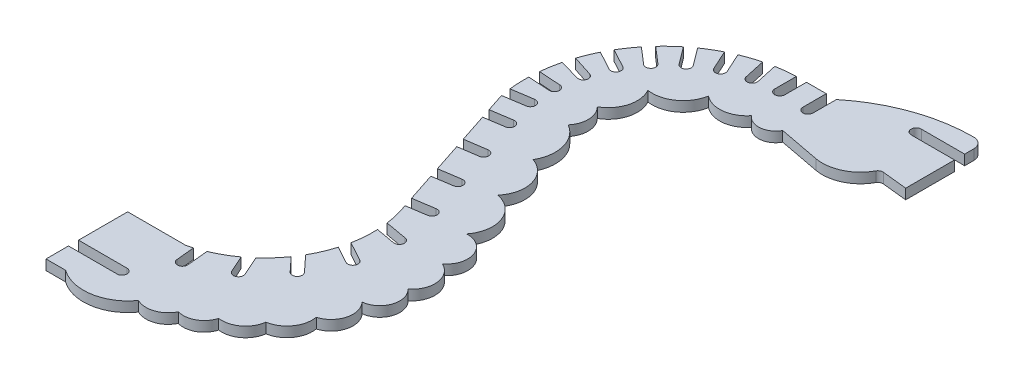
SolidWorks part; units mm, degrees
ref_plane "Front Plane" through (0, 0, 0) normal (0, 0, 1) x (1, 0, 0)
ref_plane "Top Plane" through (0, 0, 0) normal (0, 1, 0) x (1, 0, 0)
ref_plane "Right Plane" through (0, 0, 0) normal (1, 0, 0) x (0, 0, -1)
sketch "Sketch2" plane through (0, 0, 0) normal (0, 1, 0) x (1, 0, 0)
  line L0 (30.5917, -19.7066) -> (10.7781, -19.7066)
  line L1 (33.5917, -22.7066) -> (33.5917, -25.4201)
  line L2 (33.5917, -25.4201) -> (20.7417, -25.4201)
  line L3 (20.7417, -28.4201) -> (33.5917, -28.4201)
  line L4 (33.5917, -28.4201) -> (33.5917, -42.8901)
  line L5 (33.5917, -42.8901) -> (26.2103, -42.1143)
  line L6 (25.8967, -45.0978) -> (33.5917, -45.9066)
  line L7 (33.5917, -45.9066) -> (33.5917, -49.9666)
  line L8 (33.5917, -49.9666) -> (8.1291, -49.9666)
  line L9 (-13.2283, -50.6294) -> (-13.2283, -45.1294)
  line L10 (-38.0968, -90.3449) -> (-15.0449, -119.6181) construction
  line L11 (-16.2283, -45.1294) -> (-16.2283, -51.5914)
  line L12 (-21.75, -54.7438) -> (-23.977, -49.7148)
  line L13 (-26.7201, -50.9295) -> (-24.1036, -56.8382)
  line L14 (-27.876, -61.9563) -> (-31.9485, -58.2597)
  line L15 (-33.9648, -60.4811) -> (-29.18, -64.8243)
  line L16 (-30.557, -71.0316) -> (-35.7774, -69.3005)
  line L17 (-36.7216, -72.1481) -> (-30.588, -74.1819)
  line L18 (-1.8595, -49.9666) -> (0.2542, -45.786)
  line L19 (-2.4231, -44.4324) -> (-5.2212, -49.9666)
  line L20 (8.1291, -49.9666) -> (10.2428, -45.786)
  line L21 (7.5656, -44.4324) -> (4.7675, -49.9666)
  line L22 (4.7675, -49.9666) -> (-1.8595, -49.9666)
  line L23 (-5.2212, -49.9666) -> (-7.7629, -49.9666)
  line L24 (8.977, -22.5761) -> (13.5917, -32.1352)
  line L25 (-7.9083, -19.7066) -> (-7.9083, -28.4201)
  line L26 (-7.9083, -28.4201) -> (-17.7173, -27.1758)
  line L27 (-24.1872, -25.2122) -> (-23.0538, -31.1352)
  line L28 (-22.371, -24.1878) -> (-20.4329, -25.9321)
  line L29 (-38.0926, -32.0919) -> (-35.6757, -33.0702)
  line L30 (-39.4504, -33.6745) -> (-36.3639, -38.8553)
  line L31 (-23.0538, -31.1352) -> (-32.6987, -33.3127)
  line L32 (-50.1737, -44.8862) -> (-47.568, -44.981)
  line L33 (-50.9099, -46.8371) -> (-46.2408, -50.6538)
  line L34 (-36.3639, -38.8553) -> (-44.6869, -44.1931)
  line L35 (-57.1639, -61.035) -> (-54.6822, -60.235)
  line L36 (-57.1902, -63.12) -> (-51.4991, -65.1145)
  line L37 (-46.2408, -50.6538) -> (-52.2429, -58.5113)
  line L38 (-58.2242, -78.5997) -> (-56.1645, -77.001)
  line L39 (-57.5375, -80.5686) -> (-51.5074, -80.5014)
  line L40 (-51.4991, -65.1145) -> (-54.4597, -74.5484)
  line L41 (-35.2032, -82.0735) -> (-27.7919, -84.6414)
  line L42 (-34.2211, -79.2389) -> (-29.1162, -81.0076)
  line L43 (-29.3337, -80.4151) -> (-34.808, -80.9462)
  line L44 (-34.5184, -83.9321) -> (-28.0865, -83.3082)
  line L45 (-27.7919, -84.6414) -> (-23.8627, -95.4227)
  line L46 (-29.9498, -96.4886) -> (-22.5384, -99.0565)
  line L47 (-28.9676, -93.654) -> (-23.8627, -95.4227)
  line L48 (-24.6963, -110.9037) -> (-17.2849, -113.4716)
  line L49 (-23.7142, -108.0691) -> (-18.6093, -109.8378)
  line L50 (-19.4428, -125.3189) -> (-12.8043, -127.6189)
  line L51 (-18.4607, -122.4842) -> (-13.6103, -124.1647)
  line L52 (-17.6104, -135.4043) -> (-11.761, -138.9742)
  line L53 (-16.0476, -132.8435) -> (-11.8298, -135.4176)
  line L55 (-17.9659, -145.6487) -> (-13.1058, -150.2901)
  line L56 (-15.894, -143.4791) -> (-12.4305, -146.7867)
  line L57 (-13.2072, -136.8993) -> (-8.1023, -138.668)
  line L58 (-14.1894, -139.734) -> (-6.778, -142.3018)
  line L59 (-20.4932, -155.5829) -> (-16.78, -161.0812)
  line L60 (-18.0071, -153.9039) -> (-15.3857, -157.7855)
  line L61 (-25.0765, -164.7517) -> (-22.6311, -170.882)
  line L62 (-22.29, -163.6402) -> (-20.5743, -167.9412)
  line L63 (-31.5058, -172.7353) -> (-30.5908, -178.2262)
  line L64 (-28.5466, -172.2422) -> (-27.8723, -176.2883)
  line L65 (-39.4867, -179.1681) -> (-39.7092, -183.6785)
  line L66 (-36.4904, -179.3159) -> (-36.6228, -182.0006)
  line L67 (-47.9916, -182.1905) -> (-48.2552, -187.533)
  line L68 (-44.9953, -182.3383) -> (-45.1896, -186.2772)
  line L69 (-45.7574, -184.5372) -> (-47.0955, -189.4931)
  line L70 (-48.6536, -183.7552) -> (-50.485, -190.538)
  line L71 (-52.7944, -97.0434) -> (-47.044, -95.2268)
  line L72 (-54.0236, -95.3591) -> (-52.5174, -93.2307)
  line L73 (-51.5074, -80.5014) -> (-51.5989, -90.3886)
  line L74 (-48.331, -111.7688) -> (-42.5806, -109.9522)
  line L75 (-49.5602, -110.0844) -> (-48.054, -107.9561)
  line L76 (-47.044, -95.2268) -> (-47.1355, -105.1139)
  line L77 (-43.8676, -126.4942) -> (-38.1172, -124.6776)
  line L78 (-45.0969, -124.8098) -> (-43.5906, -122.6815)
  line L79 (-42.5806, -109.9522) -> (-42.6721, -119.8393)
  line L80 (-38.1172, -124.6776) -> (-38.1172, -132.1134)
  line L81 (-49.4878, -147.4069) -> (-42.6952, -147.4697)
  line L82 (-75.5719, -158.8868) -> (-75.5719, -178.7297)
  line L83 (-22.5384, -99.0565) -> (-18.6093, -109.8378)
  line L84 (-17.2849, -113.4716) -> (-15.0449, -119.6181)
  line L85 (-75.5719, -181.7068) -> (-61.4778, -181.7068)
  line L86 (-61.2167, -178.7297) -> (-75.5719, -178.7297)
  line L87 (-75.5719, -181.7068) -> (-75.5719, -190.1036)
  arc A0 (-13.2283, -45.1294) -> (-16.2283, -45.1294) centre (-14.7283, -45.1294) ccw
  arc A1 (20.7417, -25.4201) -> (20.7417, -28.4201) centre (20.7417, -26.9201) ccw
  arc A2 (26.2103, -42.1143) -> (25.8967, -45.0978) centre (26.0535, -43.6061) ccw
  arc A3 (-7.7629, -49.9666) -> (-13.2283, -50.6294) centre (-7.7629, -72.8316) ccw
  arc A4 (-15.0449, -119.6181) -> (-13.6103, -124.1647) centre (-66.1611, -138.247) cw
  arc A5 (-25.7152, -174.6342) -> (-27.8723, -176.2883) centre (-79.6425, -106.5423) cw
  arc A6 (-23.977, -49.7148) -> (-26.7201, -50.9295) centre (-25.3485, -50.3222) ccw
  arc A7 (-31.9485, -58.2597) -> (-33.9648, -60.4811) centre (-32.9567, -59.3704) ccw
  arc A8 (-35.7774, -69.3005) -> (-36.7216, -72.1481) centre (-36.2495, -70.7243) ccw
  arc A9 (0.2542, -45.786) -> (-2.4231, -44.4324) centre (-1.0844, -45.1092) ccw
  arc A10 (10.2428, -45.786) -> (7.5656, -44.4324) centre (8.9042, -45.1092) ccw
  arc A11 (-20.4329, -25.9321) -> (-17.7173, -27.1758) centre (-17.0881, -22.2156) ccw
  arc A12 (-16.2283, -51.5914) -> (-21.75, -54.7438) centre (-7.7629, -72.8316) ccw
  arc A13 (-24.1036, -56.8382) -> (-27.876, -61.9563) centre (-7.7629, -72.8316) ccw
  arc A14 (-29.18, -64.8243) -> (-30.557, -71.0316) centre (-7.7629, -72.8316) ccw
  arc A15 (-30.588, -74.1819) -> (-29.1162, -81.0076) centre (-7.7629, -72.8316) ccw
  arc A16 (13.5917, -32.1352) -> (-6.482, -19.3651) centre (14.3476, -8.7848) cw
  arc A17 (-6.482, -19.3651) -> (-7.9083, -19.7066) centre (-7.1543, -19.7066) ccw
  arc A18 (-22.371, -24.1878) -> (-24.1872, -25.2122) centre (-23.1068, -25.0054) ccw
  arc A19 (-35.6757, -33.0702) -> (-32.6987, -33.3127) centre (-33.7998, -28.4354) ccw
  arc A20 (-38.0926, -32.0919) -> (-39.4504, -33.6745) centre (-38.5053, -33.1115) ccw
  arc A21 (-47.568, -44.981) -> (-44.6869, -44.1931) centre (-47.3861, -39.9843) ccw
  arc A22 (-50.1737, -44.8862) -> (-50.9099, -46.8371) centre (-50.2137, -45.9855) ccw
  arc A23 (-54.6822, -60.235) -> (-52.2429, -58.5113) centre (-56.2163, -55.4761) ccw
  arc A24 (-57.1639, -61.035) -> (-57.1902, -63.12) centre (-56.8264, -62.0819) ccw
  arc A25 (-56.1645, -77.001) -> (-54.4597, -74.5484) centre (-59.2303, -73.0512) ccw
  arc A26 (-58.2242, -78.5997) -> (-57.5375, -80.5686) centre (-57.5498, -79.4687) ccw
  arc A27 (-34.808, -80.9462) -> (-34.5184, -83.9321) centre (-34.6632, -82.4391) ccw
  arc A28 (-35.2032, -82.0735) -> (-34.2211, -79.2389) centre (-34.7122, -80.6562) cw
  arc A29 (-29.9498, -96.4886) -> (-28.9676, -93.654) centre (-29.4587, -95.0713) cw
  arc A30 (-24.6963, -110.9037) -> (-23.7142, -108.0691) centre (-24.2052, -109.4864) cw
  arc A31 (-19.4428, -125.3189) -> (-18.4607, -122.4842) centre (-18.9518, -123.9015) cw
  arc A32 (-12.8043, -127.6189) -> (-11.8298, -135.4176) centre (-66.1611, -138.247) cw
  circle A33 centre (-7.7629, -72.8316) radius 44.4118 construction
  arc A34 (-17.6104, -135.4043) -> (-16.0476, -132.8435) centre (-16.829, -134.1239) cw
  arc A35 (-14.1894, -139.734) -> (-13.2072, -136.8993) centre (-13.6983, -138.3166) cw
  arc A36 (-17.9659, -145.6487) -> (-15.894, -143.4791) centre (-16.93, -144.5639) cw
  arc A37 (-20.4932, -155.5829) -> (-18.0071, -153.9039) centre (-19.2502, -154.7434) cw
  arc A38 (-25.0765, -164.7517) -> (-22.29, -163.6402) centre (-23.6833, -164.196) cw
  arc A39 (-31.5058, -172.7353) -> (-28.5466, -172.2422) centre (-30.0262, -172.4888) cw
  arc A40 (-39.4867, -179.1681) -> (-36.4904, -179.3159) centre (-37.9885, -179.242) cw
  arc A41 (-47.9916, -182.1905) -> (-44.9953, -182.3383) centre (-46.4934, -182.2644) cw
  arc A42 (-48.6536, -183.7552) -> (-45.7574, -184.5372) centre (-47.2055, -184.1462) cw
  arc A43 (-52.5174, -93.2307) -> (-51.5989, -90.3886) centre (-56.5987, -90.3423) ccw
  arc A44 (-54.0236, -95.3591) -> (-52.7944, -97.0434) centre (-53.1257, -95.9945) ccw
  arc A45 (-49.5602, -110.0844) -> (-48.331, -111.7688) centre (-48.6624, -110.7199) ccw
  arc A46 (-48.054, -107.9561) -> (-47.1355, -105.1139) centre (-52.1353, -105.0677) ccw
  arc A47 (-45.0969, -124.8098) -> (-43.8676, -126.4942) centre (-44.199, -125.4453) ccw
  arc A48 (-43.5906, -122.6815) -> (-42.6721, -119.8393) centre (-47.6719, -119.7931) ccw
  arc A49 (-38.1172, -132.1134) -> (-49.6306, -145.3128) centre (-51.44, -132.1134) cw
  arc A50 (-49.6306, -145.3128) -> (-49.4878, -147.4069) centre (-49.4878, -146.3549) ccw
  arc A51 (-42.6952, -147.4697) -> (-57.0275, -157.7653) centre (-53.632, -147.3685) cw
  arc A52 (-57.0275, -157.7653) -> (-77.6013, -143.4683) centre (-43.5012, -116.3489) cw
  arc A53 (-77.6013, -143.4683) -> (-80.2278, -144.5253) centre (-78.7573, -144.3877) ccw
  arc A54 (-80.2278, -144.5253) -> (-75.5719, -158.8868) centre (-45.8128, -141.3035) ccw
  arc A55 (-22.6311, -170.882) -> (-25.7152, -174.6342) centre (-66.1611, -138.247) cw
  arc A56 (-30.5908, -178.2262) -> (-36.6228, -182.0006) centre (-79.6425, -106.5423) cw
  arc A57 (-39.7092, -183.6785) -> (-45.1896, -186.2772) centre (-79.6425, -106.5423) cw
  arc A58 (-48.2552, -187.533) -> (-82.1004, -193.3675) centre (-79.6425, -106.5423) cw construction
  arc A59 (-16.78, -161.0812) -> (-20.5743, -167.9412) centre (-66.1611, -138.247) cw
  arc A60 (-13.1058, -150.2901) -> (-15.3857, -157.7855) centre (-66.1611, -138.247) cw
  arc A61 (-11.761, -138.9742) -> (-12.4305, -146.7867) centre (-66.1611, -138.247) cw
  arc A62 (-61.4778, -181.7068) -> (-61.2167, -178.7297) centre (-61.2167, -180.2297) ccw
  arc A63 (10.7781, -19.7066) -> (8.977, -22.5761) centre (10.7781, -21.7066) ccw
  arc A64 (30.5917, -19.7066) -> (33.5917, -22.7066) centre (30.5917, -22.7066) cw
  arc A65 (-48.2552, -187.533) -> (-72.3189, -193.093) centre (-79.6425, -106.5423) cw
  arc A66 (-72.3189, -193.093) -> (-75.5719, -190.1036) centre (-72.5719, -190.1036) cw
  point P30 (22.2417, -26.9201)
  point P31 (24.5617, -43.4493)
  point P36 (-14.7283, -43.6294)
  point P208 (-79.3087, -143.0175)
  point P222 (33.5917, -19.7066)
  point P223 (-75.5719, -193.3068)
  dimension "D1" = 22.865
  dimension "D4" = 54.405
  dimension "D6" = 40
  dimension "D7" = 86.86
  dimension "D12" = 1.5
  dimension "D10" = 56.11
  dimension "D22" = 41.5
  dimension "D23" = 187.229
  dimension "D25" = 1.1
  dimension "D27" = 5
  dimension "D33" = 6.1298
  dimension "D40" = 1.5
  dimension "D41" = 1.5
  dimension "D39" = 6.778
  dimension "D42" = 7.1543
  dimension "D43" = 8.1023
  dimension "D44" = 11.761
  dimension "D45" = 12.8043
  dimension "D46" = 13.2072
  dimension "D47" = 13.6103
  dimension "D48" = 15.3857
  dimension "D49" = 15.894
  dimension "D50" = 21.75
  dimension "D51" = 27.8723
  dimension "D74" = 2
  dimension "D75" = 3
  dimension "D76" = 3
  dimension "D2" = 120
  dimension "D3" = 37.26
  dimension "D5" = 62
  dimension "D8" = 46.82
  dimension "D9" = 4.06
  dimension "D11" = 9.03
  dimension "D13" = 6
  dimension "D14" = 11.35
  dimension "D15" = 30.26
  dimension "D16" = 14.47
  dimension "D17" = 7
  dimension "D21" = 20
  dimension "D24" = 10.833
  dimension "D26" = 1
  dimension "D31" = 50.35
  dimension "D32" = 4.8575
  dimension "D34" = 11.0799
  dimension "D35" = 2
  dimension "D37" = 34.42
  dimension "D38" = 11.6
  dimension "D52" = 42.6952
  dimension "D53" = 43.5012
  dimension "D54" = 44.9953
  dimension "D55" = 45.1896
  dimension "D56" = 45.8128
  dimension "D57" = 46.4934
  dimension "D58" = 49.4878
  dimension "D59" = 49.6306
  dimension "D60" = 51.44
  dimension "D61" = 53.632
  dimension "D62" = 57.0275
  dimension "D63" = 61.2167
  dimension "D64" = 61.4778
  dimension "D65" = 79.3087
  dimension "D66" = 8.7848
  dimension "D67" = 33.0668
  dimension "D68" = 72.8316
  dimension "D69" = 5.6615
  dimension "D70" = 27.1379
  dimension "D71" = 9.9886
  dimension "D72" = 5.9141
  dimension "D73" = 64.231
  dimension "D20" = 2
  dimension "D29" = 5
  dimension "D36" = 3
  dimension "D19" = 2
  dimension "D28" = 5
  dimension "D18" = 5
  dimension "D30" = 8
sketch "Sketch3" plane through (0, 0, 0) normal (0, 1, 0) x (1, 0, 0)
  line L0 (0.5917, -30.4201) -> (0.5917, -37.3301)
  line L1 (-2.4083, -37.3301) -> (-2.4083, -30.4201)
  line L2 (33.5917, -42.8901) -> (26.2103, -42.1143)
  line L3 (-2.4083, -30.4201) -> (-8.2583, -30.4201)
  line L4 (-8.2583, -30.4201) -> (-8.2583, -36.8301)
  line L5 (-11.2583, -36.8301) -> (-11.2583, -30.4201)
  line L6 (-50.0406, -78.9753) -> (-35.5907, -122.9508) construction
  line L7 (-75.5719, -178.7297) -> (-75.5719, -164.1797)
  line L8 (-75.5719, -164.1797) -> (-58.3719, -164.1797)
  line L9 (12.6752, -48.6069) -> (0.5917, -46.3094)
  line L10 (-69.7587, -188.3668) -> (-75.5719, -188.3668)
  line L11 (-75.5719, -181.7068) -> (-75.5719, -190.1036) construction
  line L12 (-75.5719, -188.3668) -> (-75.5719, -181.7068)
  line L13 (-17.0347, -31.0436) -> (-15.6668, -37.306)
  line L14 (-18.5977, -37.9462) -> (-19.9656, -31.6838)
  line L15 (-25.4759, -33.5257) -> (-22.8031, -39.3519)
  line L16 (-25.5298, -40.6028) -> (-28.2027, -34.7767)
  line L17 (-33.1929, -37.752) -> (-29.3384, -42.8736)
  line L18 (-31.7353, -44.6776) -> (-35.5899, -39.556)
  line L19 (-39.8303, -43.5278) -> (-34.9715, -47.7088)
  line L20 (-36.9283, -49.9828) -> (-41.7871, -45.8018)
  line L21 (-45.0822, -50.587) -> (-39.4431, -53.6348)
  line L22 (-40.8695, -56.274) -> (-46.5086, -53.2262)
  line L23 (-42.547, -60.3785) -> (-48.6449, -58.4179)
  line L24 (-43.3774, -63.2613) -> (-49.537, -61.4871)
  line L25 (-50.5366, -67.2104) -> (-44.1403, -67.6293)
  line L26 (-44.3363, -70.6229) -> (-50.7326, -70.204)
  line L27 (-50.4879, -76.0088) -> (-44.1496, -75.053)
  line L28 (-43.7022, -78.0195) -> (-50.0406, -78.9753)
  line L29 (-41.4565, -86.459) -> (-47.2923, -87.339)
  line L30 (-48.2422, -84.4483) -> (-41.9038, -83.4925)
  line L31 (-44.4961, -95.8486) -> (-38.1578, -94.8929)
  line L32 (-37.7105, -97.8593) -> (-43.5463, -98.7393)
  line L33 (-40.7501, -107.249) -> (-34.4118, -106.2932)
  line L34 (-33.9644, -109.2596) -> (-39.8003, -110.1397)
  line L35 (-37.0041, -118.6493) -> (-30.6657, -117.6935)
  line L36 (-30.2184, -120.66) -> (-36.0542, -121.54)
  line L37 (-28.2702, -132.7369) -> (-34.0091, -131.7223)
  line L38 (-28.8388, -142.1712) -> (-34.5612, -139.0476)
  line L39 (-30.2761, -144.8044) -> (-35.2935, -142.0656)
  line L40 (-27.7479, -129.7827) -> (-34.281, -128.6276)
  line L41 (-36.0267, -155.6016) -> (-39.8385, -151.4809)
  line L42 (-38.1772, -148.859) -> (-33.8244, -153.5644)
  line L43 (-44.921, -164.0004) -> (-47.1853, -158.9546)
  line L44 (-44.7706, -157.008) -> (-42.1839, -162.7722)
  line L45 (-56.0298, -169.1233) -> (-56.561, -163.6727)
  line L46 (-53.6505, -162.6088) -> (-53.0439, -168.8323)
  line L47 (-36.0542, -121.54) -> (-35.5907, -122.9508)
  line L48 (-37.0041, -118.6493) -> (-39.8003, -110.1397)
  line L49 (-40.7501, -107.249) -> (-43.5463, -98.7393)
  line L50 (-44.4961, -95.8486) -> (-47.2923, -87.339)
  line L51 (-50.0406, -78.9753) -> (-48.2422, -84.4483)
  line L85 (-61.2167, -178.7297) -> (-75.5719, -178.7297) construction
  line L86 (-61.2167, -178.7297) -> (-75.5719, -178.7297)
  line L167 (33.5917, -28.4201) -> (33.5917, -42.8901) construction
  line L168 (33.5917, -25.4201) -> (20.7417, -25.4201) construction
  line L169 (20.7417, -28.4201) -> (33.5917, -28.4201) construction
  line L170 (-75.5719, -181.7068) -> (-61.4778, -181.7068) construction
  line L171 (33.5917, -28.4201) -> (33.5917, -42.8901)
  line L172 (33.5917, -25.4201) -> (20.7417, -25.4201)
  line L173 (20.7417, -28.4201) -> (33.5917, -28.4201)
  line L174 (-75.5719, -181.7068) -> (-61.4778, -181.7068)
  line L175 (33.5917, -22.7066) -> (33.5917, -25.4201) construction
  line L176 (33.5917, -22.7066) -> (33.5917, -25.4201)
  line L177 (-26.4724, -132.0603) -> (-32.3082, -132.9403) [skipped]
  line L178 (-33.2581, -130.0496) -> (-26.9197, -129.0938) [skipped]
  line L179 (-34.06, -128.6667) -> (-27.7479, -129.7827) [skipped]
  line L180 (-34.4651, -139.1) -> (-28.8388, -142.1712) [skipped]
  line L181 (-48.7066, -58.6043) -> (-42.547, -60.3785) [skipped]
  arc A0 (0.5917, -37.3301) -> (-2.4083, -37.3301) centre (-0.9083, -37.3301) cw
  arc A1 (-11.2583, -30.4201) -> (-50.0406, -78.9753) centre (-9.7583, -71.384) ccw construction
  arc A2 (-8.2583, -36.8301) -> (-11.2583, -36.8301) centre (-9.7583, -36.8301) cw
  arc A3 (-35.5907, -122.9508) -> (-34.281, -128.6276) centre (-66.1287, -132.9852) cw
  arc A4 (26.2103, -42.1143) -> (24.7354, -42.8901) centre (26.0535, -43.6061) ccw
  arc A5 (26.2103, -42.1143) -> (25.8967, -45.0978) centre (26.0535, -43.6061) ccw construction
  arc A6 (24.7354, -42.8901) -> (12.6752, -48.6069) centre (14.7894, -37.4877) cw
  arc A7 (0.5917, -46.3094) -> (-7.8392, -47.1357) centre (-3.9003, -43.9005) cw
  arc A8 (-7.8392, -47.1357) -> (-19.2558, -48.4507) centre (-14.201, -42.1198) cw
  arc A9 (-19.2558, -48.4507) -> (-29.6987, -55.9722) centre (-28.2879, -46.9208) cw
  arc A10 (-29.6987, -55.9722) -> (-32.9567, -67.6854) centre (-37.1842, -60.1998) cw
  arc A11 (-32.9567, -67.6854) -> (-32.6318, -76.6309) centre (-37.6041, -72.3328) cw
  arc A12 (-32.6318, -76.6309) -> (-28.9139, -90.7425) centre (-37.8286, -85.5457) cw
  arc A13 (-28.9139, -90.7425) -> (-25.0245, -105.0718) centre (-31.7845, -99.2142) cw
  arc A14 (-25.0245, -105.0718) -> (-19.7128, -119.6469) centre (-26.7786, -113.9665) cw
  arc A15 (-19.7128, -119.6469) -> (-15.6018, -130.9272) centre (-19.3739, -125.9127) cw
  arc A16 (-15.6018, -130.9272) -> (-14.2079, -142.4872) centre (-18.432, -137.1325) cw
  arc A17 (-14.2079, -142.4872) -> (-17.7126, -152.6025) centre (-18.3166, -146.7285) cw
  arc A18 (-17.7126, -152.6025) -> (-20.5738, -163.3101) centre (-22.4043, -157.0849) cw
  arc A19 (-20.5738, -163.3101) -> (-26.7786, -172.01) centre (-28.0262, -164.5576) cw
  arc A20 (-26.7786, -172.01) -> (-34.748, -178.0488) centre (-33.7827, -171.0447) cw
  arc A21 (-34.748, -178.0488) -> (-42.4244, -182.3256) centre (-40.7246, -176.349) cw
  arc A22 (-42.4244, -182.3256) -> (-51.2266, -185.3158) centre (-48.3206, -179.4196) cw
  arc A23 (-51.2266, -185.3158) -> (-69.7587, -188.3668) centre (-62.0122, -177.6116) cw
  arc A24 (-15.6668, -37.306) -> (-18.5977, -37.9462) centre (-17.1323, -37.6261) cw
  arc A25 (-22.8031, -39.3519) -> (-25.5298, -40.6028) centre (-24.1665, -39.9774) cw
  arc A26 (-29.3384, -42.8736) -> (-31.7353, -44.6776) centre (-30.5369, -43.7756) cw
  arc A27 (-34.9715, -47.7088) -> (-36.9283, -49.9828) centre (-35.9499, -48.8458) cw
  arc A28 (-39.4431, -53.6348) -> (-40.8695, -56.274) centre (-40.1563, -54.9544) cw
  arc A29 (-42.547, -60.3785) -> (-43.3774, -63.2613) centre (-42.9622, -61.8199) cw
  arc A30 (-44.1403, -67.6293) -> (-44.3363, -70.6229) centre (-44.2383, -69.1261) cw
  arc A31 (-44.1496, -75.053) -> (-43.7022, -78.0195) centre (-43.9259, -76.5363) cw
  arc A32 (-41.9038, -83.4925) -> (-41.4565, -86.459) centre (-41.6802, -84.9758) cw
  arc A33 (-38.1578, -94.8929) -> (-37.7105, -97.8593) centre (-37.9341, -96.3761) cw
  arc A34 (-34.4118, -106.2932) -> (-33.9644, -109.2596) centre (-34.1881, -107.7764) cw
  arc A35 (-30.6657, -117.6935) -> (-30.2184, -120.66) centre (-30.4421, -119.1767) cw
  arc A36 (-27.7479, -129.7827) -> (-28.2702, -132.7369) centre (-28.009, -131.2598) cw
  arc A37 (-28.8388, -142.1712) -> (-30.2761, -144.8044) centre (-29.5574, -143.4878) cw
  arc A38 (-33.8244, -153.5644) -> (-36.0267, -155.6016) centre (-34.9255, -154.583) cw
  arc A39 (-42.1839, -162.7722) -> (-44.921, -164.0004) centre (-43.5525, -163.3863) cw
  arc A40 (-53.0439, -168.8323) -> (-56.0298, -169.1233) centre (-54.5368, -168.9778) cw
  arc A41 (-56.561, -163.6727) -> (-58.3719, -164.1797) centre (-66.1287, -132.9852) cw
  arc A42 (-47.1853, -158.9546) -> (-53.6505, -162.6088) centre (-66.1287, -132.9852) cw
  arc A43 (-39.8385, -151.4809) -> (-44.7706, -157.008) centre (-66.1287, -132.9852) cw
  arc A44 (-34.0091, -131.7223) -> (-34.5612, -139.0476) centre (-66.1287, -132.9852) cw
  arc A45 (-50.4879, -76.0088) -> (-50.7326, -70.204) centre (-9.7583, -71.384) cw
  arc A46 (-50.5366, -67.2104) -> (-49.537, -61.4871) centre (-9.7583, -71.384) cw
  arc A47 (-46.5086, -53.2262) -> (-48.6449, -58.4179) centre (-9.7583, -71.384) ccw
  arc A48 (-45.0822, -50.587) -> (-41.7871, -45.8018) centre (-9.7583, -71.384) cw
  arc A49 (-39.8303, -43.5278) -> (-35.5899, -39.556) centre (-9.7583, -71.384) cw
  arc A50 (-33.1929, -37.752) -> (-28.2027, -34.7767) centre (-9.7583, -71.384) cw
  arc A51 (-25.4759, -33.5257) -> (-19.9656, -31.6838) centre (-9.7583, -71.384) cw
  arc A52 (-17.0347, -31.0436) -> (-11.2583, -30.4201) centre (-9.7583, -71.384) cw
  arc A54 (-35.2935, -142.0656) -> (-38.1772, -148.859) centre (-66.1287, -132.9852) cw
  arc A145 (-61.4778, -181.7068) -> (-61.2167, -178.7297) centre (-61.2167, -180.2297) ccw construction
  arc A146 (-61.4778, -181.7068) -> (-61.2167, -178.7297) centre (-61.2167, -180.2297) ccw
  arc A147 (20.7417, -25.4201) -> (20.7417, -28.4201) centre (20.7417, -26.9201) ccw construction
  arc A148 (20.7417, -25.4201) -> (20.7417, -28.4201) centre (20.7417, -26.9201) ccw
  arc A149 (33.5917, -22.7066) -> (30.5917, -19.7066) centre (30.5917, -22.7066) ccw construction
  arc A150 (33.5917, -22.7066) -> (30.5917, -19.7066) centre (30.5917, -22.7066) ccw
  arc A151 (30.5917, -19.7066) -> (0.5917, -30.4201) centre (30.5917, -67.0665) ccw
  arc A152 (-26.9197, -129.0938) -> (-26.4724, -132.0603) centre (-26.6961, -130.577) cw [skipped]
  point P47 (-0.9083, -38.8301)
  point P106 (-47.6657, -55.7854)
  dimension "D3" = 1.5
  dimension "D14" = 6
  dimension "D19" = 1.5
  dimension "D25" = 5.0971
  dimension "D27" = 47.7927
  dimension "D32" = 13.2546
  dimension "D33" = 8.1013
  dimension "D34" = 6.5735
  dimension "D38" = 6.2136
  dimension "D43" = 7.0703
  dimension "D45" = 7.5561
  dimension "D46" = 6.4888
  dimension "D51" = 5.905
  dimension "D54" = 6.8202
  dimension "D57" = 6.2749
  dimension "D60" = 9.066
  dimension "D63" = 8.9448
  dimension "D66" = 10.3189
  dimension "D69" = 6.5725
  dimension "D70" = 8.5969
  dimension "D73" = 9.1607
  dimension "D1" = 33
  dimension "D2" = 2
  dimension "D4" = 8.41
  dimension "D5" = 5.85
  dimension "D6" = 0.5
  dimension "D7" = 14.55
  dimension "D8" = 17.2
  dimension "D9" = 98.575
  dimension "D12" = 5.68
  dimension "D15" = 11.4003
  dimension "D16" = 94.226
  dimension "D17" = 12.0831
  dimension "D18" = 2.8058
  dimension "D20" = 6.66
  dimension "D21" = 18.8022
  dimension "D22" = 12.0676
  dimension "D23" = 6.4128
  dimension "D24" = 37.492
  dimension "D26" = 12.0835
  dimension "D28" = 61.8796
  dimension "D29" = 70.7759
  dimension "D30" = 13.5596
  dimension "D31" = 10.7553
  dimension "D35" = 13.6917
  dimension "D36" = 8.9473
  dimension "D37" = 3.0706
  dimension "D39" = 7.596
  dimension "D40" = 6.9419
  dimension "D41" = 5.7565
  dimension "D42" = 5.3043
  dimension "D44" = 6.4871
  dimension "D47" = 7.4728
  dimension "D48" = 5.6219
  dimension "D49" = 4.0878
  dimension "D50" = 10.3564
  dimension "D52" = 9.596
  dimension "D53" = 0.1154
  dimension "D55" = 0.942
  dimension "D56" = 11.2198
  dimension "D58" = 11.9461
  dimension "D59" = 7.4047
  dimension "D61" = 5.0059
  dimension "D62" = 14.7524
  dimension "D64" = 13.6685
  dimension "D65" = 6.0441
  dimension "D67" = 13.2128
  dimension "D68" = 0.2245
  dimension "D71" = 12.1331
  dimension "D72" = 13.279
  dimension "D74" = 4.801
  dimension "D11" = 2
  dimension "D13" = 5
  dimension "D10" = 9
extrude "Boss-Extrude1" add sketch "Sketch3" along normal blind 3
